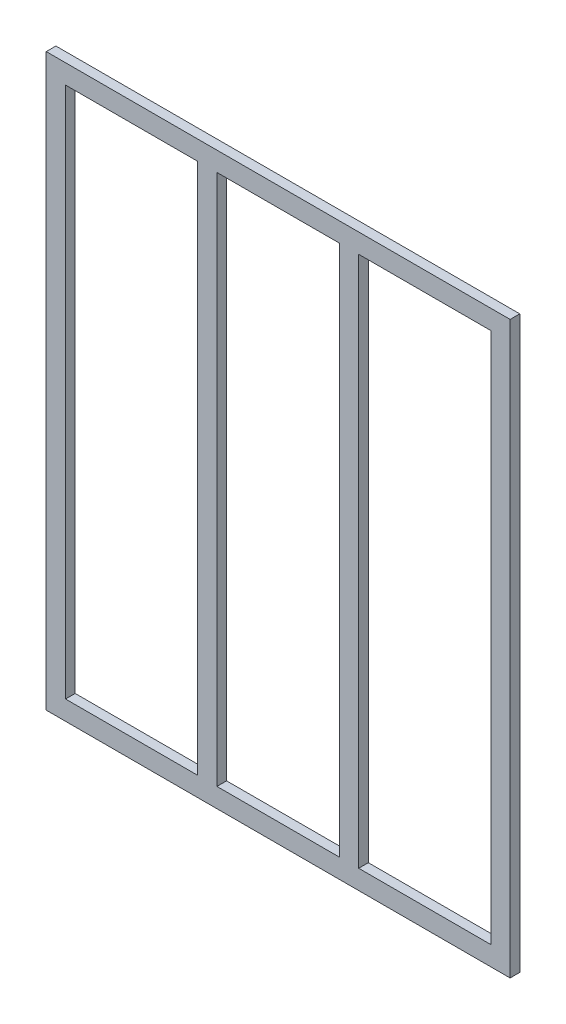
SolidWorks part; units mm, degrees
ref_plane "Alzado" through (0, 0, 0) normal (0, 0, 1) x (1, 0, 0)
ref_plane "Planta" through (0, 0, 0) normal (0, 1, 0) x (1, 0, 0)
ref_plane "Vista lateral" through (0, 0, 0) normal (1, 0, 0) x (0, 0, -1)
sketch "Croquis1" plane through (0, 0, 0) normal (0, 0, 1) x (1, 0, 0)
  line L0 (-559.2, -699.2) -> (-559.2, 699.2)
  line L1 (-610, -750) -> (610, -750)
  line L2 (-610, -750) -> (-610, 750)
  line L3 (-610, 750) -> (610, 750)
  line L4 (610, -750) -> (610, 750)
  line L5 (-610, -750) -> (610, 750) construction
  line L6 (-610, 750) -> (610, -750) construction
  line L7 (-559.2, 699.2) -> (559.2, 699.2)
  line L8 (559.2, -699.2) -> (559.2, 699.2)
  line L9 (-559.2, -699.2) -> (559.2, -699.2)
  point P0 (0, 0)
  dimension "D1" = 1500
  dimension "D2" = 1220
  dimension "D3" = 50.8
extrude "Saliente-Extruir1" add sketch "Croquis1" along normal blind 25.4
sketch "Croquis2" plane through (0, 0, 25.4) normal (0, 0, 1) x (1, 0, 0)
  line L0 (-186.4, 699.2) -> (-186.4, -699.2) construction
  line L1 (559.2, 699.2) -> (-559.2, 699.2) construction
  line L2 (-559.2, -699.2) -> (559.2, -699.2) construction
  line L3 (-559.2, 699.2) -> (-559.2, -699.2) construction
  line L4 (186.4, 699.2) -> (186.4, -699.2) construction
  line L6 (-211.8, -699.2) -> (-161, -699.2)
  line L7 (-211.8, -699.2) -> (-211.8, 699.2)
  line L8 (-211.8, 699.2) -> (-161, 699.2)
  line L9 (-161, -699.2) -> (-161, 699.2)
  line L10 (-211.8, -699.2) -> (-161, 699.2) construction
  line L11 (-211.8, 699.2) -> (-161, -699.2) construction
  line L12 (211.8, -699.2) -> (161, -699.2)
  line L13 (211.8, -699.2) -> (211.8, 699.2)
  line L14 (211.8, 699.2) -> (161, 699.2)
  line L15 (161, -699.2) -> (161, 699.2)
  line L16 (211.8, -699.2) -> (161, 699.2) construction
  line L17 (211.8, 699.2) -> (161, -699.2) construction
  point P10 (-186.4, 0)
  point P15 (186.4, 0)
  dimension "D1" = 372.8
  dimension "D2" = 372.8
  dimension "D3" = 50.8
  dimension "D4" = 50.8
extrude "Saliente-Extruir2" add sketch "Croquis2" against normal blind 25.4
